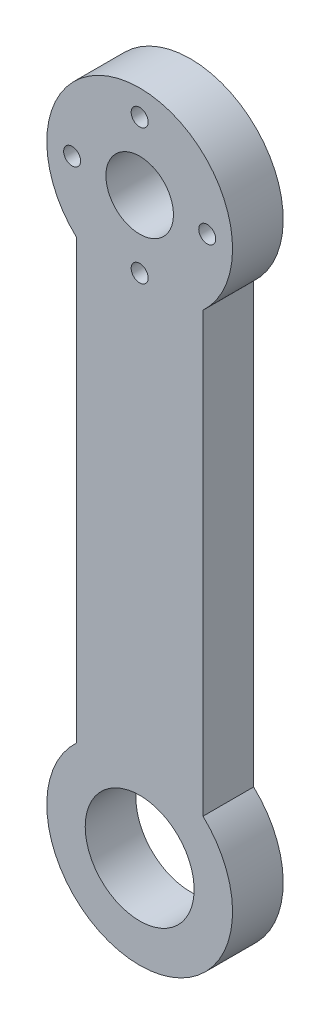
SolidWorks part; units mm, degrees
ref_plane "Plan de face" through (0, 0, 0) normal (0, 0, 1) x (1, 0, 0)
ref_plane "Plan de dessus" through (0, 0, 0) normal (0, 1, 0) x (1, 0, 0)
ref_plane "Plan de droite" through (0, 0, 0) normal (1, 0, 0) x (0, 0, -1)
sketch "Esquisse1" plane through (0, 0, 0) normal (0, 0, 1) x (1, 0, 0)
  line L1 (0, 0) -> (15, 0)
  line L2 (0, 0) -> (0, 83)
  line L3 (0, 83) -> (15, 83)
  line L4 (15, 0) -> (15, 83)
  dimension "D1" = 83
  dimension "D2" = 15
extrude "Boss.-Extru.1" add sketch "Esquisse1" along normal blind 6
sketch "Esquisse2" plane through (0, 0, 6) normal (0, 0, 1) x (1, 0, 0)
  line L0 (15, 0) -> (15, 83) construction
  line L1 (0, 0) -> (15, 0) construction
  line L2 (15, 83) -> (0, 83) construction
  line L3 (15, 0) -> (15, 83) construction
  circle A0 centre (7.5, 7.5) radius 11
  circle A1 centre (7.5, 75.5) radius 11
  dimension "D2" = 22
  dimension "D5" = 22
  dimension "D1" = 7.5
  dimension "D3" = 7.5
  dimension "D4" = 7.5
  dimension "D6" = 7.5
extrude "Boss.-Extru.2" add sketch "Esquisse2" against normal blind 6
sketch "Esquisse4" plane through (0, 0, 0) normal (0, 0, -1) x (-1, 0, 0)
  line L0 (-7.5, 86.5) -> (-7.5, 107.232) construction
  line L1 (-18.5, 75.5) -> (3.5, 75.5) construction
  circle A0 centre (-7.5, 75.5) radius 4
  circle A1 centre (-7.5, 67.5) radius 1.005
  circle A2 centre (-15.5, 75.5) radius 1.005
  circle A3 centre (-7.5, 83.5) radius 1.005
  circle A4 centre (0.5, 75.5) radius 1.005
  arc A5 (0, 67.4533) -> (-15, 67.4533) centre (-7.5, 75.5) ccw construction
  circle A6 centre (-7.5, 7.5) radius 6.45
  dimension "D1" = 8
  dimension "D2" = 8
  dimension "D3" = 8
  dimension "D4" = 8
  dimension "D6" = 2.01
  dimension "D7" = 2.01
  dimension "D8" = 2.01
  dimension "D9" = 2.01
  dimension "D10" = 12.9
  dimension "D5" = 8
extrude "Enlèv. mat.-Extru.2" cut sketch "Esquisse4" against normal blind 10
sketch "Esquisse5" plane through (0, 0, 0) normal (0, 0, -1) x (-1, 0, 0)
  circle A1 centre (-15.5, 75.5) radius 2
  circle A2 centre (-7.5, 83.5) radius 2
  circle A3 centre (0.5, 75.5) radius 2
  circle A4 centre (-7.5, 67.5) radius 2
  dimension "D2" = 4
  dimension "D3" = 4
  dimension "D4" = 4
  dimension "D5" = 4
extrude "Enlèv. mat.-Extru.3" cut sketch "Esquisse5" against normal blind 4
